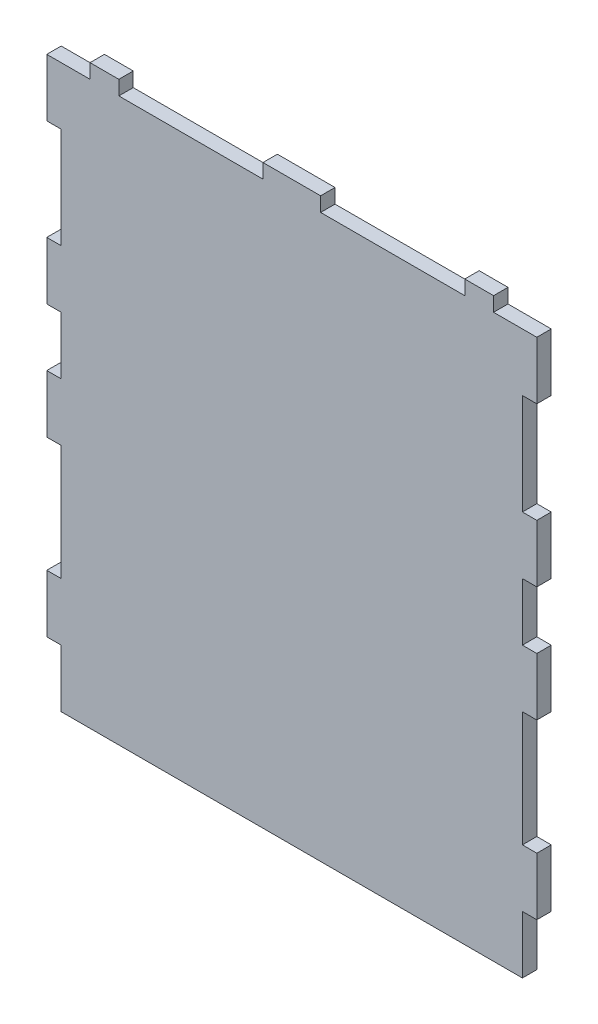
SolidWorks part; units mm, degrees
ref_plane "Front Plane" through (0, 0, 0) normal (0, 0, 1) x (1, 0, 0)
ref_plane "Top Plane" through (0, 0, 0) normal (0, 1, 0) x (1, 0, 0)
ref_plane "Right Plane" through (0, 0, 0) normal (1, 0, 0) x (0, 0, -1)
sketch "Sketch1" plane through (0, 0, 0) normal (0, 0, 1) x (1, 0, 0)
  line L0 (10, 97.5) -> (35, 97.5)
  line L1 (0, 0) -> (80, 0)
  line L2 (0, 0) -> (0, 10)
  line L3 (0, 97.5) -> (5, 97.5)
  line L4 (80, 0) -> (80, 10)
  line L5 (45, 97.5) -> (70, 97.5)
  line L6 (5, 97.5) -> (5, 100)
  line L7 (5, 100) -> (10, 100)
  line L8 (10, 97.5) -> (10, 100)
  line L9 (75, 97.5) -> (80, 97.5)
  line L10 (35, 97.5) -> (35, 100)
  line L11 (35, 100) -> (45, 100)
  line L12 (45, 97.5) -> (45, 100)
  line L13 (80, 20) -> (80, 40)
  line L14 (70, 97.5) -> (70, 100)
  line L15 (70, 100) -> (75, 100)
  line L16 (75, 97.5) -> (75, 100)
  line L17 (80, 97.5) -> (82.5, 97.5)
  line L19 (80, 87.5) -> (82.5, 87.5)
  line L20 (82.5, 97.5) -> (82.5, 87.5)
  line L21 (80, 70) -> (82.5, 70)
  line L22 (80, 70) -> (80, 87.5)
  line L23 (80, 60) -> (82.5, 60)
  line L24 (82.5, 70) -> (82.5, 60)
  line L25 (80, 50) -> (82.5, 50)
  line L26 (40, 0) -> (40, 32.346) construction
  line L27 (80, 40) -> (82.5, 40)
  line L28 (82.5, 50) -> (82.5, 40)
  line L29 (80, 20) -> (82.5, 20)
  line L30 (80, 50) -> (80, 60)
  line L31 (80, 10) -> (82.5, 10)
  line L32 (82.5, 20) -> (82.5, 10)
  line L33 (-2.5, 20) -> (-2.5, 10)
  line L34 (0, 10) -> (-2.5, 10)
  line L35 (0, 20) -> (-2.5, 20)
  line L36 (-2.5, 50) -> (-2.5, 40)
  line L37 (0, 40) -> (-2.5, 40)
  line L38 (0, 50) -> (-2.5, 50)
  line L39 (-2.5, 70) -> (-2.5, 60)
  line L40 (0, 60) -> (-2.5, 60)
  line L41 (0, 70) -> (-2.5, 70)
  line L42 (-2.5, 97.5) -> (-2.5, 87.5)
  line L43 (0, 87.5) -> (-2.5, 87.5)
  line L44 (0, 97.5) -> (-2.5, 97.5)
  line L45 (0, 20) -> (0, 40)
  line L46 (0, 50) -> (0, 60)
  line L47 (0, 70) -> (0, 87.5)
  point P1 (0, 0)
  dimension "D3" = 5
  dimension "D4" = 5
  dimension "D5" = 25
  dimension "D6" = 5
  dimension "D7" = 10
  dimension "D8" = 5
  dimension "D9" = 2.5
  dimension "D11" = 10
  dimension "D12" = 2.5
  dimension "D13" = 10
  dimension "D14" = 10
  dimension "D15" = 10
  dimension "D16" = 17.5
  dimension "D17" = 10
  dimension "D18" = 20
  dimension "D2" = 100
  dimension "D10" = 80
extrude "Boss-Extrude1" add sketch "Sketch1" along normal blind 2.5
equation "\"width\"=80"
equation "\"bottom_depth\"=100"
equation "\"t\"=2.5"
equation "\"D9@Sketch1\"=\"t\""
equation "\"D1@Boss-Extrude1\"=\"t\""
equation "\"D12@Sketch1\"=\"t\""
